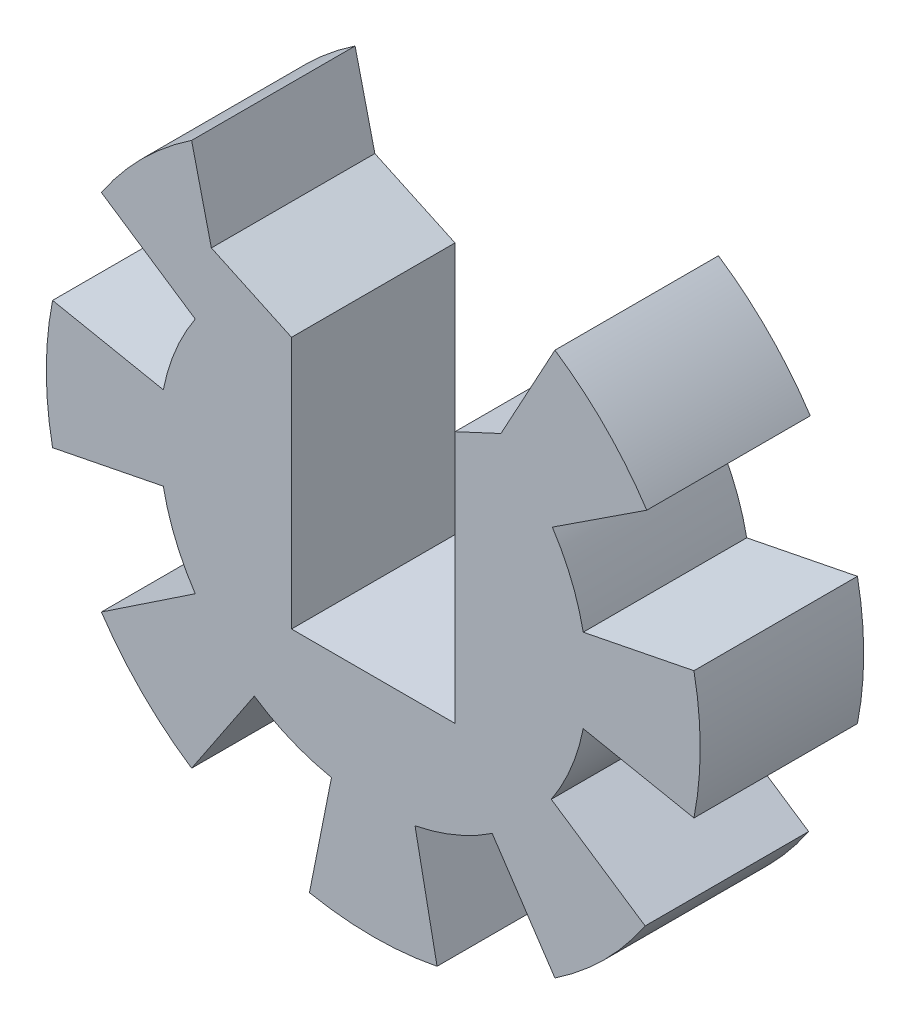
SolidWorks part; units mm, degrees
ref_plane "Plano frontal" through (0, 0, 0) normal (0, 0, 1) x (1, 0, 0)
ref_plane "Plano superior" through (0, 0, 0) normal (0, 1, 0) x (1, 0, 0)
ref_plane "Plano direito" through (0, 0, 0) normal (1, 0, 0) x (0, 0, -1)
sketch "Esboço1" plane through (0, 0, 0) normal (0, 0, 1) x (1, 0, 0)
  line L4 (-3, -3.7191) -> (3, -3.7191)
  line L5 (-11, 0) -> (12, 0) construction
  line L6 (0, 0) -> (0, -12) construction
  line L7 (-8.4853, 8.4853) -> (8.4853, -8.4853) construction
  line L8 (-8.4853, -8.4853) -> (8.4853, 8.4853) construction
  line L9 (-5.9412, 6.9226) -> (-3, 5.5527)
  line L12 (4.5922, -11.0866) -> (0, 0) construction
  line L13 (-11.0866, -4.5922) -> (11.0866, 4.5922) construction
  line L24 (-4.5922, -11.0866) -> (0, 0) construction
  line L25 (-11.0866, 4.5922) -> (11.0866, -4.5922) construction
  line L42 (2.3411, -11.7694) -> (1.5328, -7.7061)
  line L43 (3, 5.5527) -> (4.687, 6.3384)
  line L44 (-3, 5.5527) -> (-3, -3.7191)
  line L45 (3, 5.5527) -> (3, -3.7191)
  line L46 (-2.3411, -11.7694) -> (-1.5328, -7.7061)
  line L47 (-9.9776, -6.6668) -> (-6.5329, -4.3652)
  line L48 (-6.6668, -9.9776) -> (-4.3652, -6.5329)
  line L49 (-11.7694, 2.3411) -> (-7.7061, 1.5328)
  line L50 (-11.7694, -2.3411) -> (-7.7061, -1.5328)
  line L51 (-6.6668, 9.9776) -> (-5.9412, 6.9226)
  line L52 (-9.9776, 6.6668) -> (-6.5329, 4.3652)
  line L55 (10.0378, 6.576) -> (6.5723, 4.3057)
  line L56 (6.6668, 9.9776) -> (4.687, 6.3384)
  line L57 (11.7694, -2.3411) -> (7.7061, -1.5328)
  line L58 (11.7694, 2.3411) -> (7.7061, 1.5328)
  line L59 (6.6668, -9.9776) -> (4.3652, -6.5329)
  line L60 (9.9776, -6.6668) -> (6.5329, -4.3652)
  arc A3 (-8.4853, 8.4853) -> (8.4853, 8.4853) centre (0, 0) ccw construction
  arc A5 (0, -12) -> (2.3411, -11.7694) centre (0, 0) ccw
  arc A6 (0, -12) -> (-2.3411, -11.7694) centre (0, 0) cw
  arc A7 (-8.4853, -8.4853) -> (-9.9776, -6.6668) centre (0, 0) cw
  arc A8 (-8.4853, -8.4853) -> (-6.6668, -9.9776) centre (0, 0) ccw
  arc A9 (-12, 0) -> (-11.7694, 2.3411) centre (0, 0) cw
  arc A10 (-12, 0) -> (-11.7694, -2.3411) centre (0, 0) ccw
  arc A11 (-8.4853, 8.4853) -> (-6.6668, 9.9776) centre (0, 0) cw
  arc A12 (-8.4853, 8.4853) -> (-9.9776, 6.6668) centre (0, 0) ccw
  arc A13 (-6.5329, 4.3652) -> (-7.7061, 1.5328) centre (0, 0) ccw
  arc A14 (-7.7061, -1.5328) -> (-6.5329, -4.3652) centre (0, 0) ccw
  arc A15 (8.8657, 8.087) -> (10.0378, 6.576) centre (0, 0) cw
  arc A16 (8.8657, 8.087) -> (6.6668, 9.9776) centre (0, 0) ccw
  arc A17 (12, 0) -> (11.7694, -2.3411) centre (0, 0) cw
  arc A18 (12, 0) -> (11.7694, 2.3411) centre (0, 0) ccw
  arc A19 (8.4853, -8.4853) -> (6.6668, -9.9776) centre (0, 0) cw
  arc A20 (8.4853, -8.4853) -> (9.9776, -6.6668) centre (0, 0) ccw
  arc A21 (-4.3652, -6.5329) -> (-1.5328, -7.7061) centre (0, 0) ccw
  arc A22 (1.5328, -7.7061) -> (4.3652, -6.5329) centre (0, 0) ccw
  arc A23 (6.5329, -4.3652) -> (7.7061, -1.5328) centre (0, 0) ccw
  arc A24 (7.259, 3.0068) -> (6.5723, 4.3057) centre (0, 0) ccw
  arc A25 (7.259, 3.0068) -> (7.7061, 1.5328) centre (0, 0) cw
  point P42 (9.7378, 1.937)
  point P64 (0, 0)
  dimension "D2" = 9.2719
  dimension "D13" = 11.25
  dimension "D14" = 11.25
  dimension "D4" = 3.14
  dimension "D10" = 7.8571
  dimension "D3" = 6
  dimension "D16" = 4.1429
  dimension "D5" = 9.2719
  dimension "D6" = 22.5
  dimension "D7" = 45
  dimension "D8" = 22.5
  dimension "D9" = 22.5
  dimension "D11" = 22.5
extrude "Ressalto-extrusão1" add sketch "Esboço1" along normal blind 6
